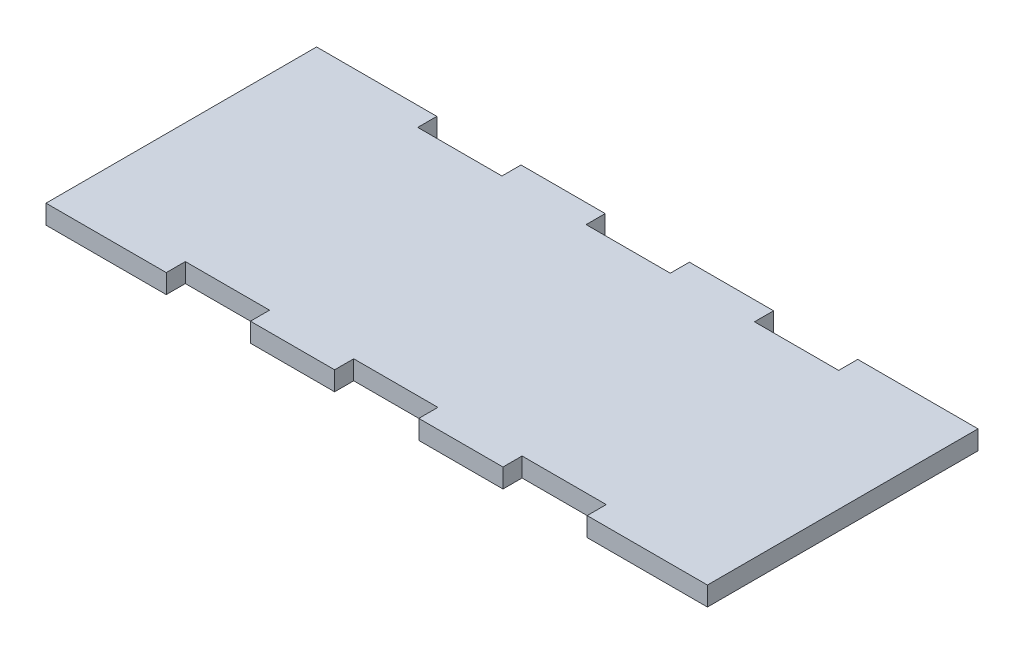
SolidWorks part; units mm, degrees
material "Mahogany"
ref_plane "Front Plane" through (0, 0, 0) normal (0, 0, 1) x (1, 0, 0)
ref_plane "Top Plane" through (0, 0, 0) normal (0, 1, 0) x (1, 0, 0)
ref_plane "Right Plane" through (0, 0, 0) normal (1, 0, 0) x (0, 0, -1)
sketch "Sketch3" plane through (0, 0, 0) normal (0, 1, 0) x (1, 0, 0)
  line L0 (20, 45) -> (20, 0) construction
  line L1 (0, 0) -> (20, 0)
  line L2 (0, 0) -> (0, 45)
  line L3 (0, 45) -> (20, 45)
  line L4 (110, 0) -> (110, 45)
  line L5 (90, 45) -> (90, 0) construction
  line L6 (90, 45) -> (110, 45)
  line L7 (90, 0) -> (110, 0)
  line L8 (20, 45) -> (90, 45) construction
  line L9 (20, 45) -> (20, 41.825)
  line L10 (20, 0) -> (90, 0) construction
  line L11 (20, 41.825) -> (34, 41.825)
  line L12 (34, 41.825) -> (34, 45)
  line L13 (20, 0) -> (20, 3.175)
  line L14 (20, 3.175) -> (34, 3.175)
  line L15 (34, 3.175) -> (34, 0)
  line L16 (48, 45) -> (48, 41.825)
  line L17 (48, 41.825) -> (62, 41.825)
  line L18 (48, 0) -> (48, 3.175)
  line L19 (48, 3.175) -> (62, 3.175)
  line L20 (62, 3.175) -> (62, 0)
  line L21 (62, 41.825) -> (62, 45)
  line L22 (76, 45) -> (76, 41.825)
  line L23 (76, 41.825) -> (90, 41.825)
  line L24 (76, 0) -> (76, 3.175)
  line L25 (76, 3.175) -> (90, 3.175)
  line L26 (90, 3.175) -> (90, 0)
  line L27 (90, 41.825) -> (90, 45)
  line L28 (34, 45) -> (48, 45)
  line L29 (62, 45) -> (76, 45)
  line L30 (34, 0) -> (48, 0)
  line L31 (62, 0) -> (76, 0)
  text T0 "FRONT"
  dimension "D1" = 45
  dimension "D2" = 20
  dimension "D3" = 20
  dimension "D4" = 70
  dimension "D5" = 14
  dimension "D6" = 3.175
  dimension "D8" = 14
  dimension "D7" = 3
extrude "Boss-Extrude1" add sketch "Sketch3" along normal blind 3.175 contours L20 L31 L24 L25 L26 L7 L4 L6 L27 L23 L22 L29 L21 L17 L16 L28 L12 L11 L9 L3 L2 L1 L13 L14 L15 L30 L18 L19
equation "\"T\"= 0.125in'Material Thickness"
equation "\"L_f\"= 20mm'Length of front platform"
equation "\"L_m\"= 70mm'Lenght of mid platform"
equation "\"L_b\"= 20mm'Length of back platform"
equation "\"L_f_t\"= 5mm'Length of front indent on top"
equation "\"L_b_t\"= 15mm'Length of back indent on top"
equation "\"L_m_t\"= \"L_m\" - \"L_b_t\" - \"L_f_t\"'Length of top platform"
equation "\"W\"= 45mm'Width of basket"
equation "\"H\"= 30mm'Height of basket"
equation "\"W_min\"= round ( 1.25 * \"T\" )'Minimum width of parts"
equation "\"D1@Sketch3\"=\"W\""
equation "\"D2@Sketch3\"=\"L_b\""
equation "\"D3@Sketch3\"=\"L_f\""
equation "\"D4@Sketch3\"=\"L_m\""
equation "\"D5@Sketch3\"=\"L_m\"/5"
equation "\"D6@Sketch3\"=\"T\""
equation "\"D8@Sketch3\"=\"L_m\"/5"
equation "\"D1@Boss-Extrude1\"=\"T\""
